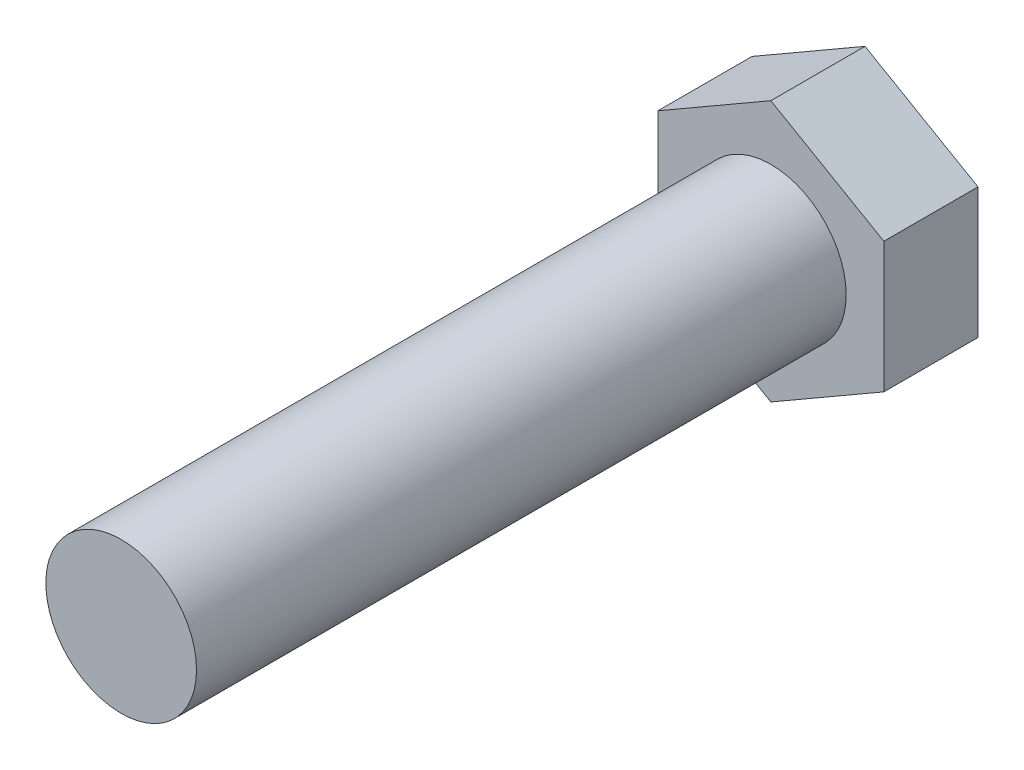
SolidWorks part; units mm, degrees
material "Alloy Steel (SS)"
ref_plane "Front Plane" through (0, 0, 0) normal (0, 0, 1) x (1, 0, 0)
ref_plane "Top Plane" through (0, 0, 0) normal (0, 1, 0) x (1, 0, 0)
ref_plane "Right Plane" through (0, 0, 0) normal (1, 0, 0) x (0, 0, -1)
sketch "Sketch1" plane through (0, 0, 0) normal (0, 0, 1) x (1, 0, 0)
  line L0 (0, 0) -> (0, 6.9282) construction
  line L2 (0, 6.9282) -> (-6, 3.4641)
  line L3 (-6, 3.4641) -> (-6, -3.4641)
  line L4 (-6, -3.4641) -> (0, -6.9282)
  line L5 (0, -6.9282) -> (6, -3.4641)
  line L6 (6, -3.4641) -> (6, 3.4641)
  line L7 (6, 3.4641) -> (0, 6.9282)
  circle A0 centre (0, 0) radius 6 construction
  circle A1 centre (0, 0) radius 4 construction
  dimension "D1" = 8
  dimension "D2" = 2
extrude "Boss-Extrude1" add sketch "Sketch1" along normal blind 5
sketch "Sketch2" plane through (0, 0, 5) normal (0, 0, 1) x (1, 0, 0)
  circle A0 centre (0, 0) radius 4
  circle A1 centre (0, 0) radius 4 construction
extrude "Boss-Extrude2" add sketch "Sketch2" along normal blind 34.5
cosmetic thread "Cosmetic Thread1" parameters "D1"=7, "D2"=6.891
